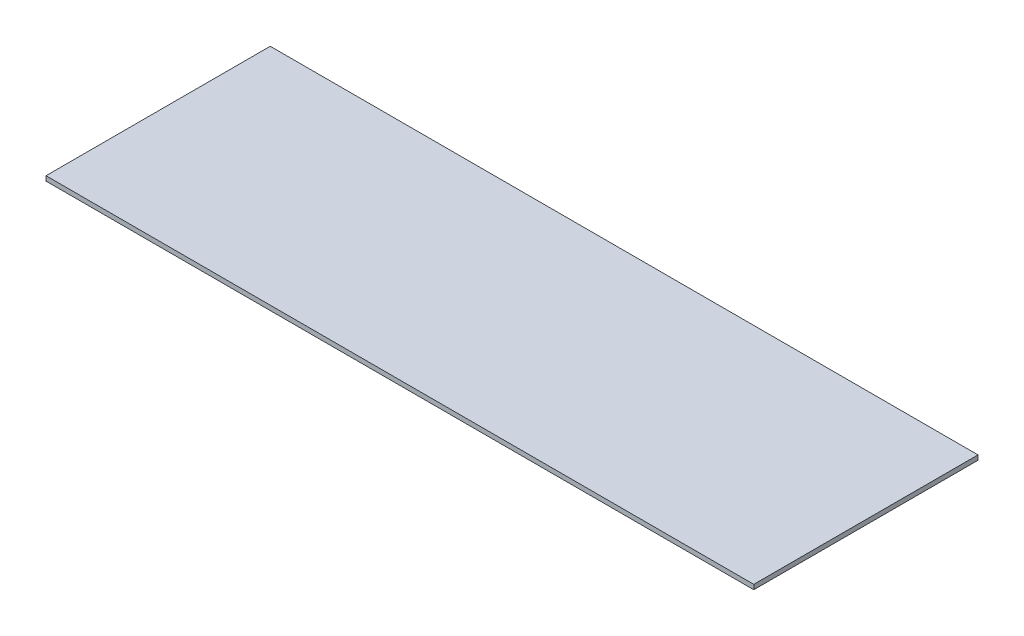
SolidWorks part; units mm, degrees
ref_plane "Front Plane" through (0, 0, 0) normal (0, 0, 1) x (1, 0, 0)
ref_plane "Top Plane" through (0, 0, 0) normal (0, 1, 0) x (1, 0, 0)
ref_plane "Right Plane" through (0, 0, 0) normal (1, 0, 0) x (0, 0, -1)
sketch "Sketch1" plane through (0, 0, 0) normal (0, 1, 0) x (1, 0, 0)
  line L0 (-119.6944, 37.9212) -> (119.6944, -37.9212) construction
  line L1 (-119.6944, 37.9212) -> (119.6944, 37.9212)
  line L2 (-119.6944, 37.9212) -> (-119.6944, -37.9212)
  line L3 (-119.6944, -37.9212) -> (119.6944, -37.9212)
  line L4 (119.6944, 37.9212) -> (119.6944, -37.9212)
  line L5 (119.6944, -37.9212) -> (120.7986, -37.5531) construction
extrude "Boss-Extrude1" add sketch "Sketch1" against normal blind 1.5875
